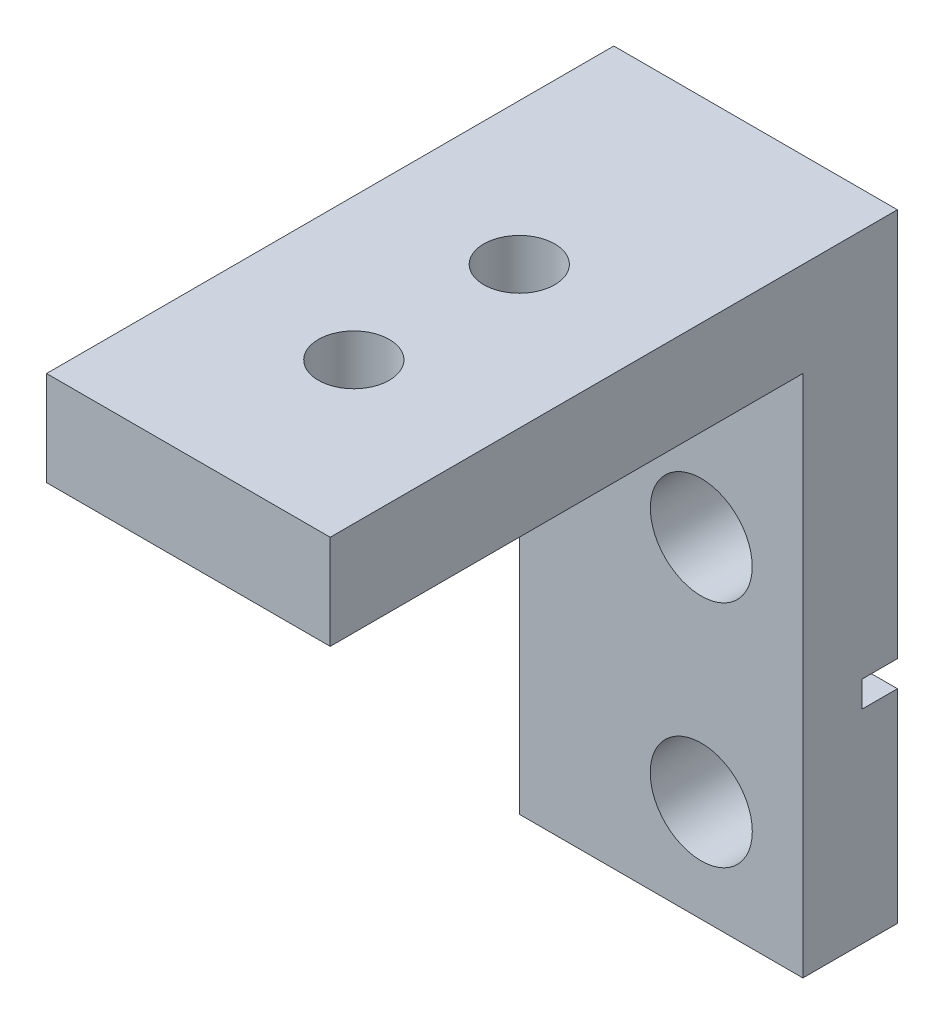
SolidWorks part; units mm, degrees
ref_plane "前视基准面" through (0, 0, 0) normal (0, 0, 1) x (1, 0, 0)
ref_plane "上视基准面" through (0, 0, 0) normal (0, 1, 0) x (1, 0, 0)
ref_plane "右视基准面" through (0, 0, 0) normal (1, 0, 0) x (0, 0, -1)
sketch "草图1" plane through (0, 0, 0) normal (0, 0, 1) x (1, 0, 0)
  line L1 (6, -11.1) -> (-6, -11.1)
  line L2 (6, -11.1) -> (6, 11.1)
  line L3 (6, 11.1) -> (-6, 11.1)
  line L4 (-6, -11.1) -> (-6, 11.1)
  line L5 (6, -11.1) -> (-6, 11.1) construction
  line L6 (6, 11.1) -> (-6, -11.1) construction
  point P0 (0, 0)
  dimension "D1" = 12
  dimension "D2" = 22.2
extrude "凸台-拉伸1" add sketch "草图1" along normal blind 4
sketch "草图2" plane through (0, 0, 4) normal (0, 0, 1) x (1, 0, 0)
  line L0 (6, -11.1) -> (6, 11.1) construction
  line L1 (-6, -11.1) -> (6, -11.1) construction
  circle A0 centre (1.7, -6.8) radius 2.16
  circle A1 centre (1.7, 2.9) radius 2.155
  dimension "D1" = 4.3
  dimension "D3" = 4.32
  dimension "D4" = 9.7
  dimension "D5" = 4.31
  dimension "D2" = 4.3
extrude "切除-拉伸1" cut sketch "草图2" against normal blind 4
sketch "草图4" plane through (0, 0, 0) normal (0, 0, -1) x (-1, 0, 0)
  line L0 (-1.7, 2.9) -> (-1.7, -6.8) construction
  line L1 (-1.7, -6.8) -> (-1.7, -2.5)
  line L2 (-1.7, 2.9) -> (-1.7, -1.4) construction
  line L3 (-6, -2.5) -> (-1.7, -2.5)
  line L4 (-6, -11.1) -> (-6, 11.1) construction
  line L5 (-1.7, -2.5) -> (6, -2.5)
  line L6 (6, 11.1) -> (6, -11.1) construction
  line L7 (-6, -1.4) -> (-1.7, -1.4)
  line L8 (-1.7, -1.4) -> (6, -1.4)
  line L9 (-6, -1.4) -> (-6, -2.5)
  line L10 (6, -1.4) -> (6, -2.5)
  line M11 (6, -11.1) -> (6, 11.1)
  line M13 (-6, 11.1) -> (-6, -11.1)
  dimension "D1" = 4.3
  dimension "D2" = 4.3
extrude "切除-拉伸2" cut sketch "草图4" against normal blind 1.5 contours L8 L7 L3 L5 M13 M11
sketch "草图5" plane through (0, 0, 0) normal (0, 0, -1) x (-1, 0, 0)
  line L1 (-6, 11.1) -> (7.3874, 11.1)
  line L2 (-6, 11.1) -> (-6, 7.2)
  line L3 (-6, 7.2) -> (7.3874, 7.2)
  line L4 (7.3874, 11.1) -> (7.3874, 7.2)
  circle A0 centre (-1.7, 2.9) radius 2.155 construction
  dimension "D1" = 4.3
extrude "切除-拉伸3" cut sketch "草图5" against normal through all contours L2 L1 L4 L3
sketch "草图6" plane through (0, 0, 4) normal (0, 0, 1) x (1, 0, 0)
  line L0 (-6, 7.2) -> (-6, -11.1) construction
  line L1 (6, 7.2) -> (-6, 7.2)
  line L2 (6, 7.2) -> (6, 15.05)
  line L3 (6, 15.05) -> (-6, 15.05)
  line L4 (-6, 7.2) -> (-6, 15.05)
  line L5 (6, 7.2) -> (-6, 15.05) construction
  line L6 (6, 15.05) -> (-6, 7.2) construction
  line L7 (6, 7.2) -> (-6, 7.2) construction
  line L8 (6, -11.1) -> (6, 7.2) construction
  circle A0 centre (1.7, 2.9) radius 2.155 construction
  point P0 (0, 11.125)
  dimension "D1" = 12.15
extrude "凸台-拉伸3" add sketch "草图6" against normal blind 4
sketch "草图7" plane through (0, 0, 4) normal (0, 0, 1) x (1, 0, 0)
  line L0 (6, -11.1) -> (6, 15.05) construction
  line L1 (-6, 15.05) -> (6, 15.05)
  line L2 (-6, 15.05) -> (-6, 11.05)
  line L3 (-6, 11.05) -> (6, 11.05)
  line L4 (6, 15.05) -> (6, 11.05)
  dimension "D1" = 4
extrude "凸台-拉伸4" add sketch "草图7" along normal blind 20
sketch "草图8" plane through (0, 11.05, 0) normal (0, -1, 0) x (1, 0, 0)
  line L0 (-6, 4) -> (6, 4) construction
  line L1 (6, 24) -> (6, 4) construction
  circle A0 centre (0, 10) radius 1.5
  circle A1 centre (0, 17) radius 1.5
  dimension "D1" = 6
  dimension "D5" = 3
  dimension "D6" = 3
  dimension "D2" = 6
  dimension "D3" = 7
  dimension "D4" = 6
extrude "切除-拉伸4" cut sketch "草图8" against normal through all
